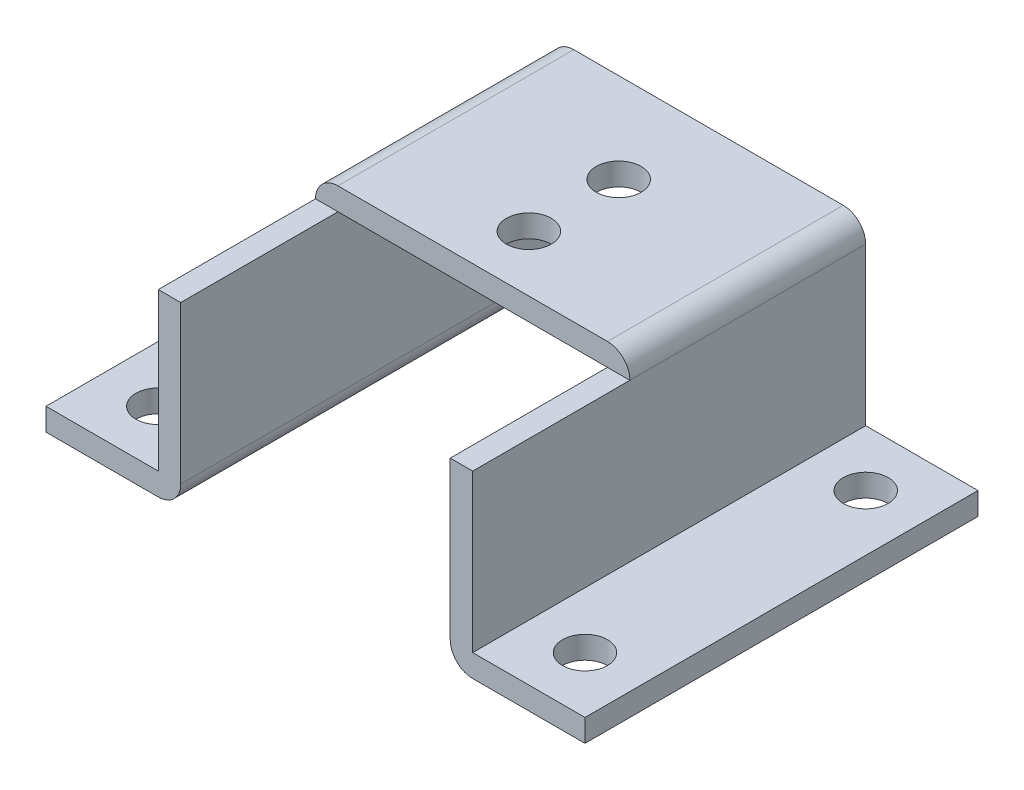
SolidWorks part; units mm, degrees
ref_plane "Front Plane" through (0, 0, 0) normal (0, 0, 1) x (1, 0, 0)
ref_plane "Top Plane" through (0, 0, 0) normal (0, 1, 0) x (1, 0, 0)
ref_plane "Right Plane" through (0, 0, 0) normal (1, 0, 0) x (0, 0, -1)
sketch "Sketch1" plane through (0, 0, 0) normal (0, 0, 1) x (1, 0, 0)
  line L0 (-12, 3.175) -> (-12, -12.825)
  line L1 (-12, 3.175) -> (12, 3.175)
  line L3 (-24, -12.825) -> (-12, -12.825)
  line L5 (12, 3.175) -> (12, -12.825)
  line L6 (12, -12.825) -> (24, -12.825)
  line L7 (-24, -10.825) -> (-14, -10.825)
  line L8 (-14, 5.175) -> (-14, -10.825)
  line L9 (-14, 5.175) -> (14, 5.175)
  line L10 (14, 5.175) -> (14, -10.825)
  line L11 (14, -10.825) -> (24, -10.825)
  line L12 (-24, -10.825) -> (-24, -12.825)
  line L13 (24, -10.825) -> (24, -12.825)
  point P0 (0, 0)
  dimension "D1" = 16
  dimension "D2" = 2
extrude "Boss-Extrude1" add sketch "Sketch1" against normal blind 35
fillet "Fillet1" radius 2 1 edges at (-14, 5.175, -17.5)
fillet "Fillet2" radius 2 1 edges at (14, 5.175, -17.5)
sketch "Sketch4" plane through (0, 5.175, 0) normal (0, 1, 0) x (1, 0, 0)
  line L1 (-14, 0) -> (14, 0)
  line L2 (-14, 14) -> (14, 14)
  line L3 (-14, 14) -> (-14, 0)
  line L4 (14, 14) -> (14, 0)
  point P8 (-24, 14)
  point P9 (24, 14)
extrude "Cut-Extrude2" cut sketch "Sketch4" against normal blind 2
fillet "Fillet3" radius 2 1 edges at (12, -12.825, -17.5)
fillet "Fillet4" radius 2 1 edges at (-12, -12.825, -17.5)
hole_wizard "Ø4.0 (4) Diameter Hole1" positions "Sketch10" profile "Sketch11" hole size "Ø4.0" standard "DIN" end condition through all
sketch "Sketch10" plane through (0, 5.175, 0) normal (0, 1, 0) x (1, 0, 0)
  line L0 (-14, 35) -> (-24, 35) construction
  line L2 (12, 35) -> (-12, 35) construction
  point P0 (-19, 30)
  point P2 (-19, 5)
  point P4 (0, 27)
  point P6 (0, 19)
  point P8 (19, 30)
  point P10 (19, 5)
  point P24 (0, 0)
  dimension "D1" = 25
  dimension "D2" = 5
  dimension "D3" = 38
  dimension "D4" = 8
  dimension "D5" = 8
  dimension "D6" = 19
  dimension "D7" = 19
sketch "Sketch11" plane through (-19, 5.175, -30) normal (1, 0, 0) x (0, 0, 1)
  line L0 (0, 0) -> (0, 18)
  line L1 (0, 18) -> (2, 18)
  line L2 (2, 18) -> (2, 0)
  line L5 (2, 0) -> (0, 0)
  line L11 (0, -6.35) -> (0, 107.95) construction
  dimension "Thru Hole Dia." = 4
  dimension "Thru Hole Depth" = 18
